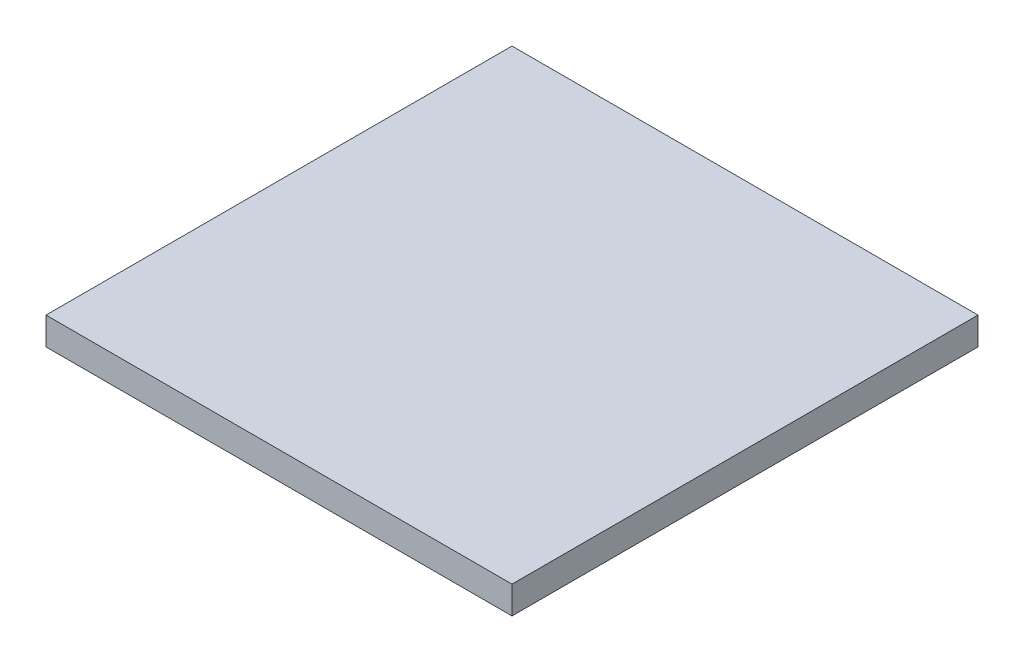
SolidWorks part; units mm, degrees
ref_plane "Front Plane" through (0, 0, 0) normal (0, 0, 1) x (1, 0, 0)
ref_plane "Top Plane" through (0, 0, 0) normal (0, 1, 0) x (1, 0, 0)
ref_plane "Right Plane" through (0, 0, 0) normal (1, 0, 0) x (0, 0, -1)
sketch "Sketch1" plane through (0, 0, 0) normal (0, 0, 1) x (1, 0, 0)
  line L1 (-812.8, 48.1178) -> (812.8, 48.1178)
  line L2 (-812.8, 48.1178) -> (-812.8, -48.1178)
  line L3 (-812.8, -48.1178) -> (812.8, -48.1178)
  line L4 (812.8, 48.1178) -> (812.8, -48.1178)
  line L5 (-812.8, 48.1178) -> (812.8, -48.1178) construction
  line L6 (-812.8, -48.1178) -> (812.8, 48.1178) construction
  point P0 (0, 0)
  dimension "D1" = 1625.6
extrude "Boss-Extrude1" add sketch "Sketch1" along normal blind 1625.6
